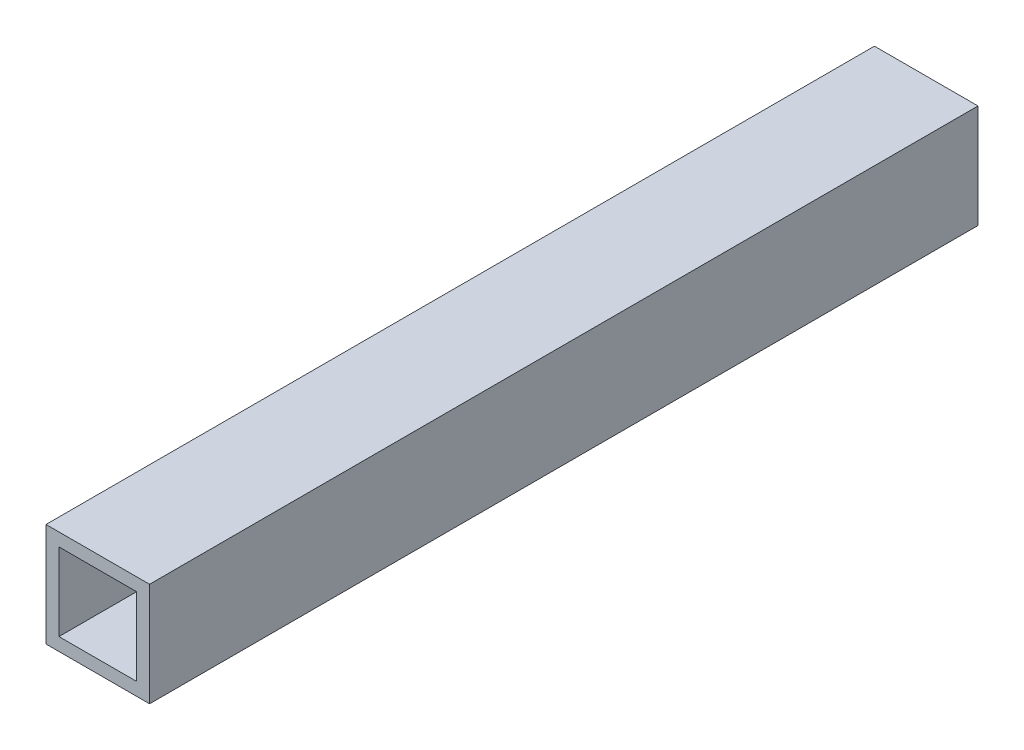
SolidWorks part; units mm, degrees
material "6061 Alloy"
ref_plane "Front" through (0, 0, 0) normal (0, 0, 1) x (1, 0, 0)
ref_plane "Top" through (0, 0, 0) normal (0, 1, 0) x (1, 0, 0)
ref_plane "Right" through (0, 0, 0) normal (1, 0, 0) x (0, 0, -1)
sketch "Sketch1" plane through (0, 0, 0) normal (0, 0, 1) x (1, 0, 0)
  line L1 (0, 0) -> (-25.4, 0)
  line L2 (0, 0) -> (0, 25.4)
  line L3 (0, 25.4) -> (-25.4, 25.4)
  line L4 (-25.4, 0) -> (-25.4, 25.4)
  dimension "D1" = 25.4
extrude "Extrude-Thin1" add sketch "Sketch1" along normal blind 203.2 thin
